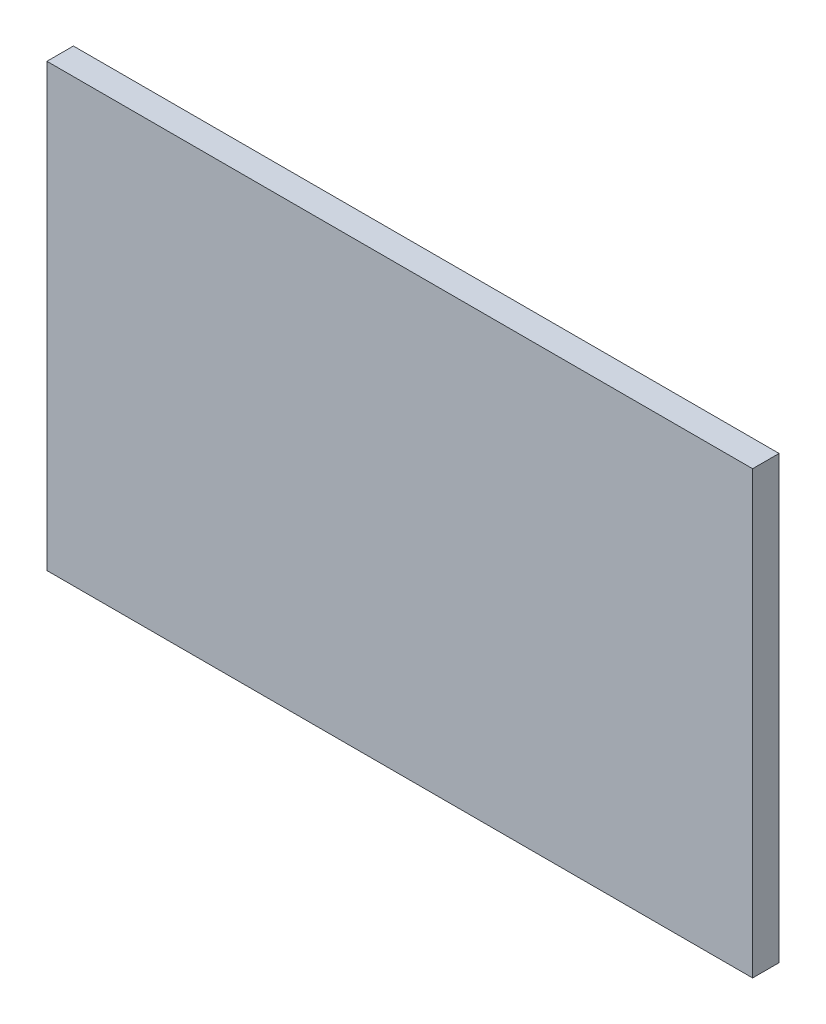
SolidWorks part; units mm, degrees
ref_plane "Front Plane" through (0, 0, 0) normal (0, 0, 1) x (1, 0, 0)
ref_plane "Top Plane" through (0, 0, 0) normal (0, 1, 0) x (1, 0, 0)
ref_plane "Right Plane" through (0, 0, 0) normal (1, 0, 0) x (0, 0, -1)
sketch "Sketch1" plane through (0, 0, 0) normal (0, 0, 1) x (1, 0, 0)
  line L0 (-40, 0) -> (40, 0) construction
  line L1 (40, -25) -> (-40, -25)
  line L2 (40, -25) -> (40, 25)
  line L3 (40, 25) -> (-40, 25)
  line L4 (-40, -25) -> (-40, 25)
  line L5 (40, -25) -> (-40, 25) construction
  line L6 (40, 25) -> (-40, -25) construction
  point P0 (0, 0)
  dimension "80" = 80
  dimension "D2" = 50
extrude "Boss-Extrude1" add sketch "Sketch1" along normal blind 3
